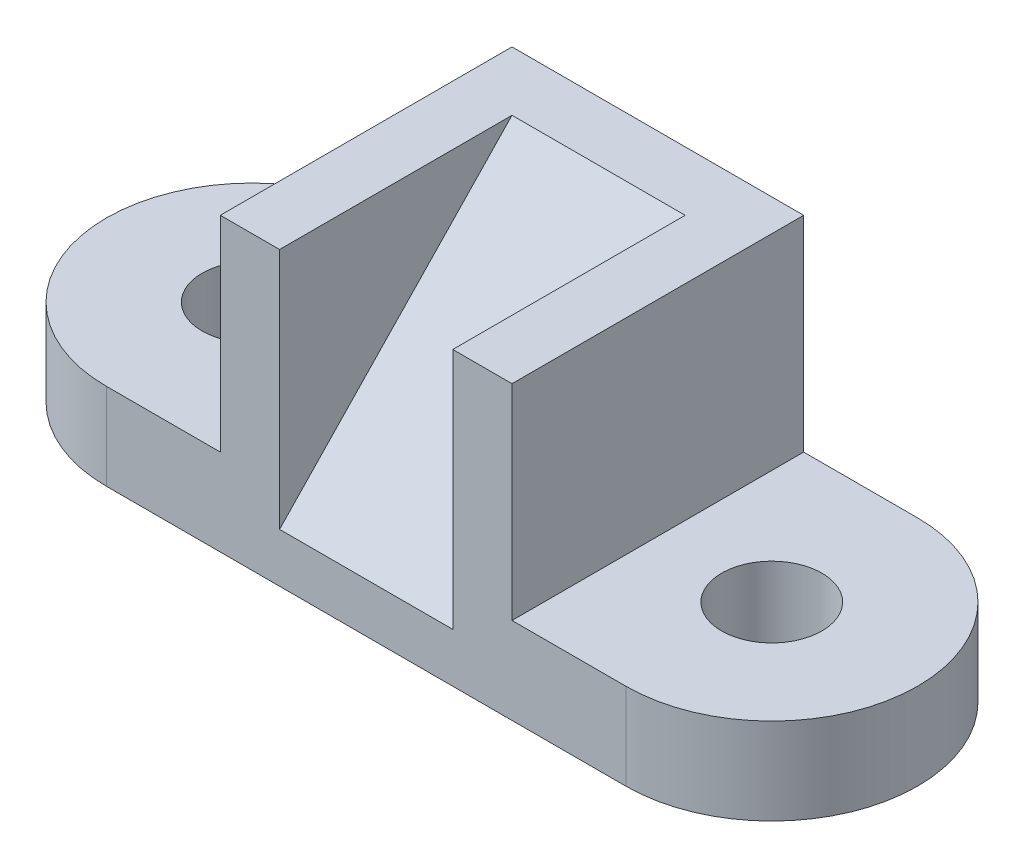
SolidWorks part; units mm, degrees
ref_plane "Front Plane" through (0, 0, 0) normal (0, 0, 1) x (1, 0, 0)
ref_plane "Top Plane" through (0, 0, 0) normal (0, 1, 0) x (1, 0, 0)
ref_plane "Right Plane" through (0, 0, 0) normal (1, 0, 0) x (0, 0, -1)
sketch "Sketch2" plane through (0, 0, 0) normal (0, 1, 0) x (1, 0, 0)
  line L0 (-57, 0) -> (57, 0) construction
  line L2 (-57, 32) -> (57, 32)
  line L3 (-57, -32) -> (57, -32)
  arc A0 (-57, 32) -> (-57, -32) centre (-57, 0) ccw
  arc A1 (57, -32) -> (57, 32) centre (57, 0) ccw
  circle A2 centre (-57, 0) radius 11
  circle A3 centre (57, 0) radius 11
  point P5 (0, 0)
  dimension "D2" = 32
  dimension "D3" = 22
  dimension "D4" = 22
  dimension "D1" = 114
extrude "Boss-Extrude4" add sketch "Sketch2" along normal blind 19
sketch "Sketch3" plane through (0, 19, 0) normal (0, 1, 0) x (1, 0, 0)
  line L1 (-32, 32) -> (32, 32)
  line L2 (-32, 32) -> (-32, -32)
  line L3 (-32, -32) -> (32, -32)
  line L4 (32, 32) -> (32, -32)
  line L5 (-32, 32) -> (32, -32) construction
  line L6 (-32, -32) -> (32, 32) construction
  point P0 (0, 0)
  dimension "D1" = 64
  dimension "D2" = 64
extrude "Boss-Extrude5" add sketch "Sketch3" along normal blind 45 contours L2 L1 L4 L3
sketch "Sketch6" plane through (-32, 0, 0) normal (-1, 0, 0) x (0, 0, 1)
  line L0 (-19, 64) -> (32, 10.8133)
  line L1 (-32, 64) -> (32, 64) construction
  line L2 (32, 19) -> (32, 0) construction
  line L3 (32, 10.8133) -> (32, 64)
  line L4 (32, 64) -> (-19, 64)
  dimension "D1" = 13
  dimension "D2" = 10.8133
extrude "Cut-Extrude1" cut sketch "Sketch6" against normal blind 38 from offset 13 contours L4 L0 L3
